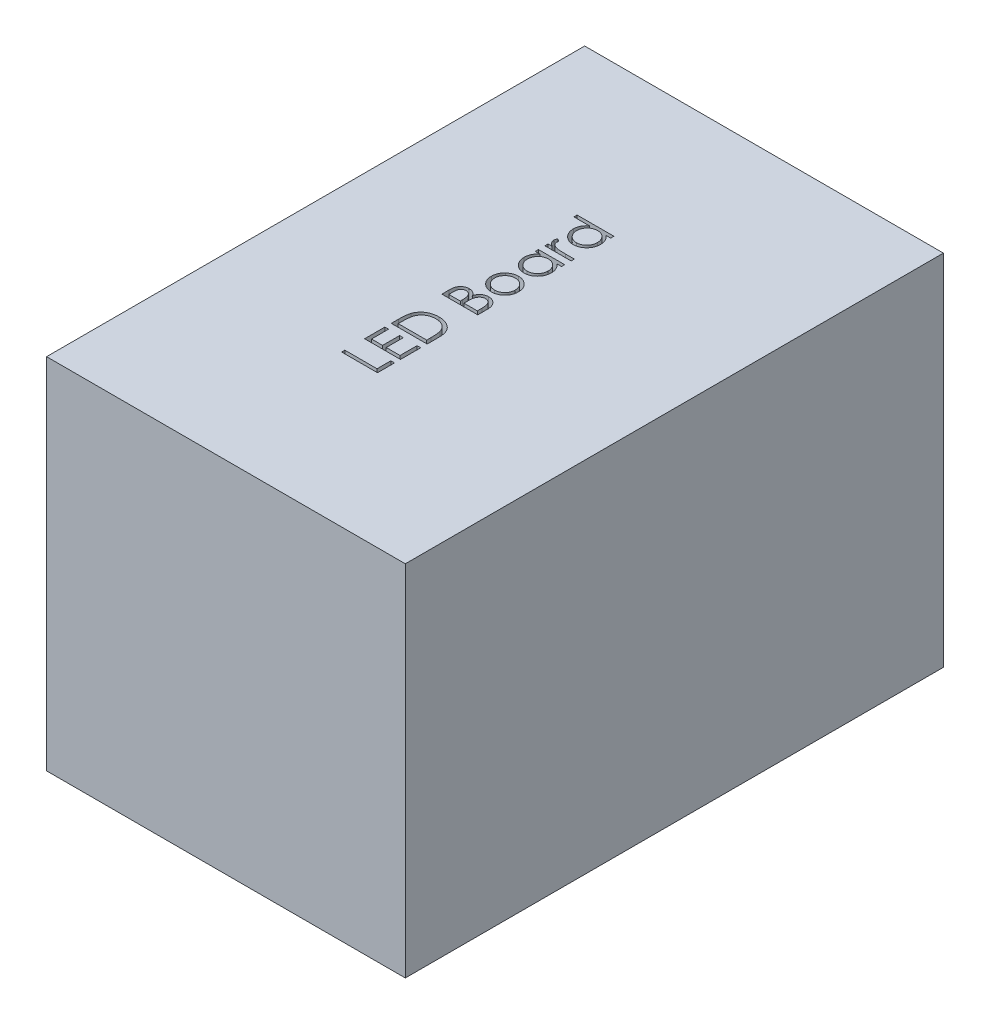
SolidWorks part; units mm, degrees
ref_plane "Front Plane" through (0, 0, 0) normal (0, 0, 1) x (1, 0, 0)
ref_plane "Top Plane" through (0, 0, 0) normal (0, 1, 0) x (1, 0, 0)
ref_plane "Right Plane" through (0, 0, 0) normal (1, 0, 0) x (0, 0, -1)
sketch "Sketch1" plane through (0, 0, 0) normal (0, 1, 0) x (1, 0, 0)
  line L1 (-10, 15) -> (10, 15)
  line L2 (-10, 15) -> (-10, -15)
  line L3 (-10, -15) -> (10, -15)
  line L4 (10, 15) -> (10, -15)
  line L5 (-10, 15) -> (10, -15) construction
  line L6 (-10, -15) -> (10, 15) construction
  point P0 (0, 0)
  dimension "D1" = 20
  dimension "D2" = 30
extrude "Boss-Extrude1" add sketch "Sketch1" along normal blind 20
sketch "Sketch2" plane through (0, 20, 0) normal (0, 1, 0) x (1, 0, 0)
  line L0 (0, -15) -> (0, 15) construction
  line L1 (-10, -15) -> (10, -15) construction
  line L2 (10, 15) -> (-10, 15) construction
  text T0 "LED Board" font "Century Gothic" height 2
extrude "Cut-Extrude1" cut sketch "Sketch2" against normal blind 2
